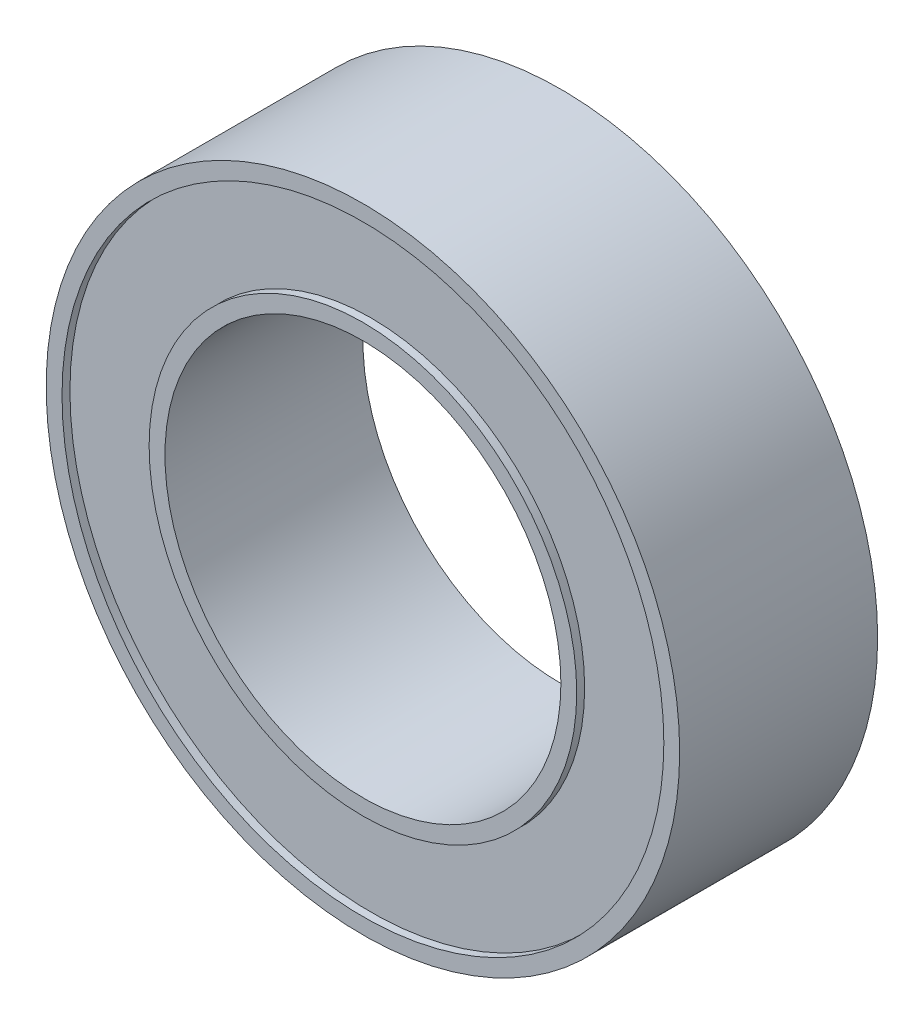
SolidWorks part; units mm, degrees
ref_plane "Front Plane" through (0, 0, 0) normal (0, 0, 1) x (1, 0, 0)
ref_plane "Top Plane" through (0, 0, 0) normal (0, 1, 0) x (1, 0, 0)
ref_plane "Right Plane" through (0, 0, 0) normal (1, 0, 0) x (0, 0, -1)
sketch "Sketch1" plane through (0, 0, 0) normal (0, 0, 1) x (1, 0, 0)
  circle A0 centre (0, 0) radius 4
  circle A1 centre (0, 0) radius 2.5
  dimension "D1" = 8
  dimension "D2" = 5
extrude "Boss-Extrude1" add sketch "Sketch1" along normal mid plane 2.5
sketch "Sketch2" plane through (0, 0, 1.25) normal (0, 0, 1) x (1, 0, 0)
  circle A2 centre (0, 0) radius 3.8
  circle A3 centre (0, 0) radius 3.8
  circle A5 centre (0, 0) radius 2.7
  circle A6 centre (0, 0) radius 2.7
  dimension "D1" = 0.2
  dimension "D2" = 0.2
extrude "Cut-Extrude1" cut sketch "Sketch2" against normal blind 0.1
mirror "Mirror1" about plane through (0, 0, 0) normal (0, 0, 1) of "Cut-Extrude1"
